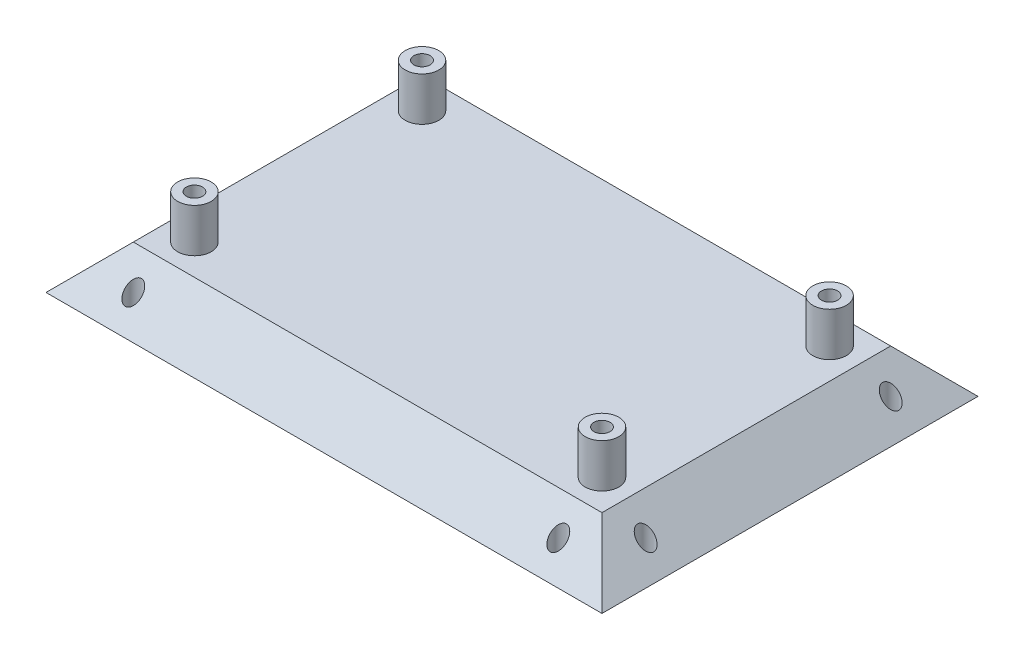
SolidWorks part; units mm, degrees
ref_plane "Спереди" through (0, 0, 0) normal (0, 0, 1) x (1, 0, 0)
ref_plane "Сверху" through (0, 0, 0) normal (0, 1, 0) x (1, 0, 0)
ref_plane "Справа" through (0, 0, 0) normal (1, 0, 0) x (0, 0, -1)
sketch "Sketch1" plane through (0, 0, 0) normal (0, 1, 0) x (1, 0, 0)
  line L1 (0, 0) -> (127.3501, 0)
  line L2 (0, 0) -> (0, -86.1254)
  line L3 (0, -86.1254) -> (127.3501, -86.1254)
  line L4 (127.3501, 0) -> (127.3501, -86.1254)
ref_plane "Plane1" through (0, 10, 0) normal (0, 1, 0) x (1, 0, 0)
sketch "Sketch2" plane through (0, 10, 0) normal (0, 1, 0) x (1, 0, 0)
  line L8 (10, -10) -> (10, -76.1254)
  line L9 (117.3501, -10) -> (10, -10)
  line L10 (117.3501, -76.1254) -> (117.3501, -10)
  line L11 (10, -76.1254) -> (117.3501, -76.1254)
  line L12 (10, -10) -> (10, -76.1254)
  line L13 (117.3501, -10) -> (10, -10)
  line L14 (117.3501, -76.1254) -> (117.3501, -10)
  line L15 (10, -76.1254) -> (117.3501, -76.1254)
  dimension "D1" = 10
loft "Loft1" add profiles "Sketch1", "Sketch2"
sketch "Sketch3" plane through (0, 0, 0) normal (0, -1, 0) x (1, 0, 0)
  line L0 (10, 10) -> (117.3501, 10) construction
  line L1 (0, 0) -> (127.3501, 0) construction
  line L2 (0, 0) -> (0, 86.1254) construction
  line L3 (0, 86.1254) -> (127.3501, 86.1254) construction
  line L4 (127.3501, 0) -> (127.3501, 86.1254) construction
  line L5 (117.3501, 10) -> (117.3501, 76.1254) construction
  line L6 (10, 76.1254) -> (117.3501, 76.1254) construction
  line L7 (10, 10) -> (10, 76.1254) construction
  line L8 (10, 10) -> (5, 10) construction
  line L9 (5, 10) -> (5, 15) construction
  line L10 (5, 15) -> (5, 20) construction
  line L11 (5, 20) -> (10, 20) construction
  line L12 (5, 15) -> (0, 15) construction
  line L13 (5, 15) -> (10, 15) construction
  line L14 (63.675, 0) -> (63.675, 86.1254) construction
  line L15 (0, 43.0627) -> (127.3501, 43.0627) construction
  line L16 (0, 0) -> (10, 10) construction
  circle A0 centre (5, 15) radius 1.85
  circle A1 centre (5, 71.1254) radius 1.85
  circle A2 centre (122.3501, 71.1254) radius 1.85
  circle A3 centre (122.3501, 15) radius 1.85
  circle A4 centre (15, 5) radius 1.85
  circle A5 centre (15, 81.1254) radius 1.85
  circle A6 centre (112.3501, 81.1254) radius 1.85
  circle A7 centre (112.3501, 5) radius 1.85
  dimension "D2" = 3.7
  dimension "D3" = 10
  dimension "D1" = 10
extrude "Cut-Extrude1" cut sketch "Sketch3" against normal through all
sketch "Sketch4" plane through (0, 10, 0) normal (0, 1, 0) x (1, 0, 0)
  line L0 (110.3501, -69.1254) -> (110.3501, -76.1254) construction
  line L1 (10, -76.1254) -> (117.3501, -76.1254) construction
  line L2 (110.3501, -69.1254) -> (117.3501, -69.1254) construction
  line L3 (117.3501, -76.1254) -> (117.3501, -10) construction
  line L4 (117.3501, -43.0627) -> (10, -43.0627) construction
  line L5 (10, -10) -> (10, -76.1254) construction
  line L6 (63.675, -76.1254) -> (63.675, -10) construction
  line L7 (117.3501, -10) -> (10, -10) construction
  circle A0 centre (110.3501, -69.1254) radius 1.85
  circle A1 centre (110.3501, -69.1254) radius 3.85
  circle A2 centre (110.3501, -17) radius 3.85
  circle A3 centre (110.3501, -17) radius 1.85
  circle A4 centre (17, -17) radius 1.85
  circle A5 centre (17, -17) radius 3.85
  circle A6 centre (17, -69.1254) radius 3.85
  circle A7 centre (17, -69.1254) radius 1.85
  dimension "D1" = 3.7
  dimension "D3" = 7
  dimension "D4" = 7
  dimension "D2" = 2
extrude "Boss-Extrude1" add sketch "Sketch4" along normal blind 10
